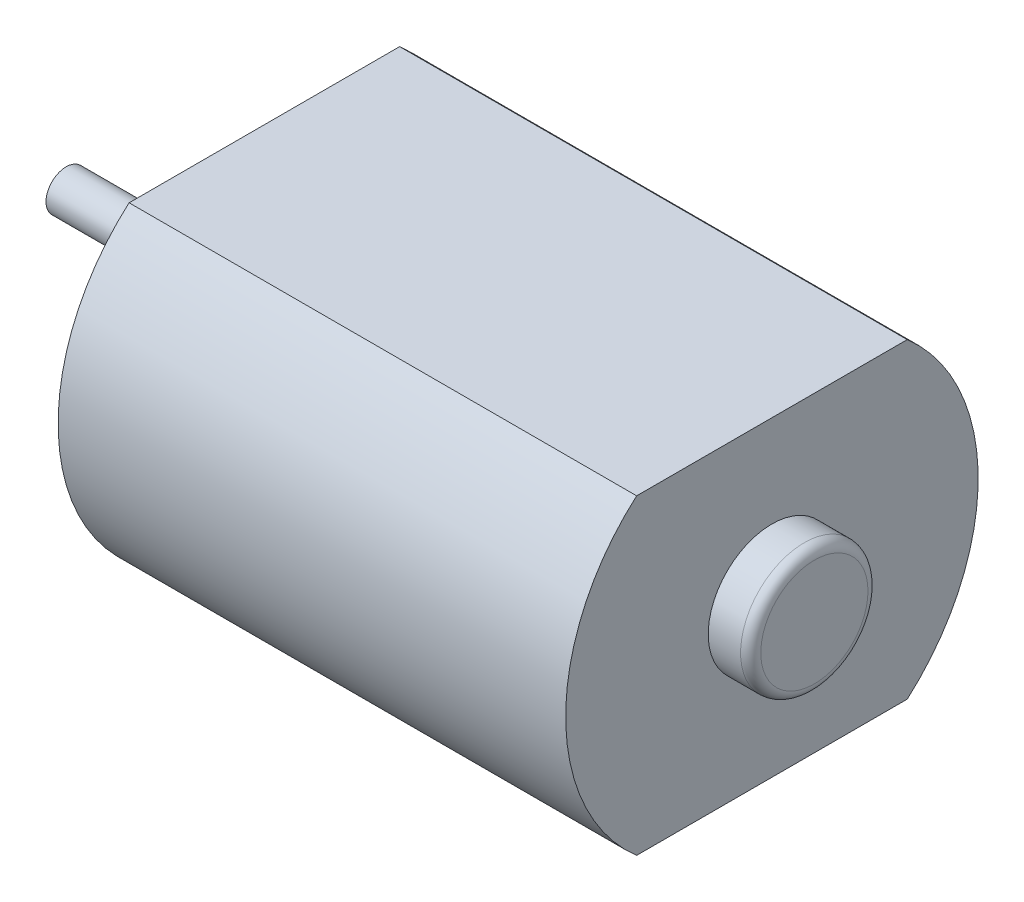
SolidWorks part; units mm, degrees
ref_plane "前视基准面" through (0, 0, 0) normal (0, 0, 1) x (1, 0, 0)
ref_plane "上视基准面" through (0, 0, 0) normal (0, 1, 0) x (1, 0, 0)
ref_plane "右视基准面" through (0, 0, 0) normal (1, 0, 0) x (0, 0, -1)
sketch "草图1" plane through (0, 0, 0) normal (1, 0, 0) x (0, 0, -1)
  circle A0 centre (0, 0) radius 10.2
  dimension "D1" = 20.4
extrude "凸台-拉伸1" add sketch "草图1" along normal blind 25.1
sketch "草图2" plane through (0, 0, 0) normal (-1, 0, 0) x (0, 0, 1)
  line L1 (-14.9975, 7.7) -> (14.9975, 7.7)
  line L2 (-14.9975, 7.7) -> (-14.9975, -7.7)
  line L3 (-14.9975, -7.7) -> (14.9975, -7.7)
  line L4 (14.9975, 7.7) -> (14.9975, -7.7)
  line L5 (-14.9975, 7.7) -> (14.9975, -7.7) construction
  line L6 (-14.9975, -7.7) -> (14.9975, 7.7) construction
  point P0 (0, 0)
  dimension "D1" = 15.4
extrude "切除-拉伸1" cut sketch "草图2" against normal blind 54.1 flip side to cut
sketch "草图3" plane through (25.1, 0, 0) normal (1, 0, 0) x (0, 0, -1)
  circle A0 centre (0, 0) radius 3.15
  dimension "D1" = 6.3
extrude "凸台-拉伸2" add sketch "草图3" along normal blind 2.1
fillet "圆角1" radius 0.5 1 edges at (27.2, 0, -3.15)
sketch "草图4" plane through (0, 0, 0) normal (-1, 0, 0) x (0, 0, 1)
  circle A0 centre (0, 0) radius 3.075
  dimension "D1" = 6.15
extrude "凸台-拉伸3" add sketch "草图4" along normal blind 1.7
sketch "草图6" plane through (0, 0, 0) normal (-1, 0, 0) x (0, 0, 1)
  circle A0 centre (0, 0) radius 1
  dimension "D1" = 2
extrude "凸台-拉伸4" add sketch "草图6" along normal blind 9.8
sketch "草图7" plane through (0, 0, 0) normal (-1, 0, 0) x (0, 0, 1)
  line L0 (-6.2, 0) -> (6.2, 0) construction
  circle A0 centre (6.2, 0) radius 1.1
  circle A1 centre (-6.2, 0) radius 1.1
  point P5 (0, 0)
  dimension "D2" = 2.2
  dimension "D3" = 2.2
  dimension "D1" = 12.4
extrude "切除-拉伸2" cut sketch "草图7" against normal blind 3
